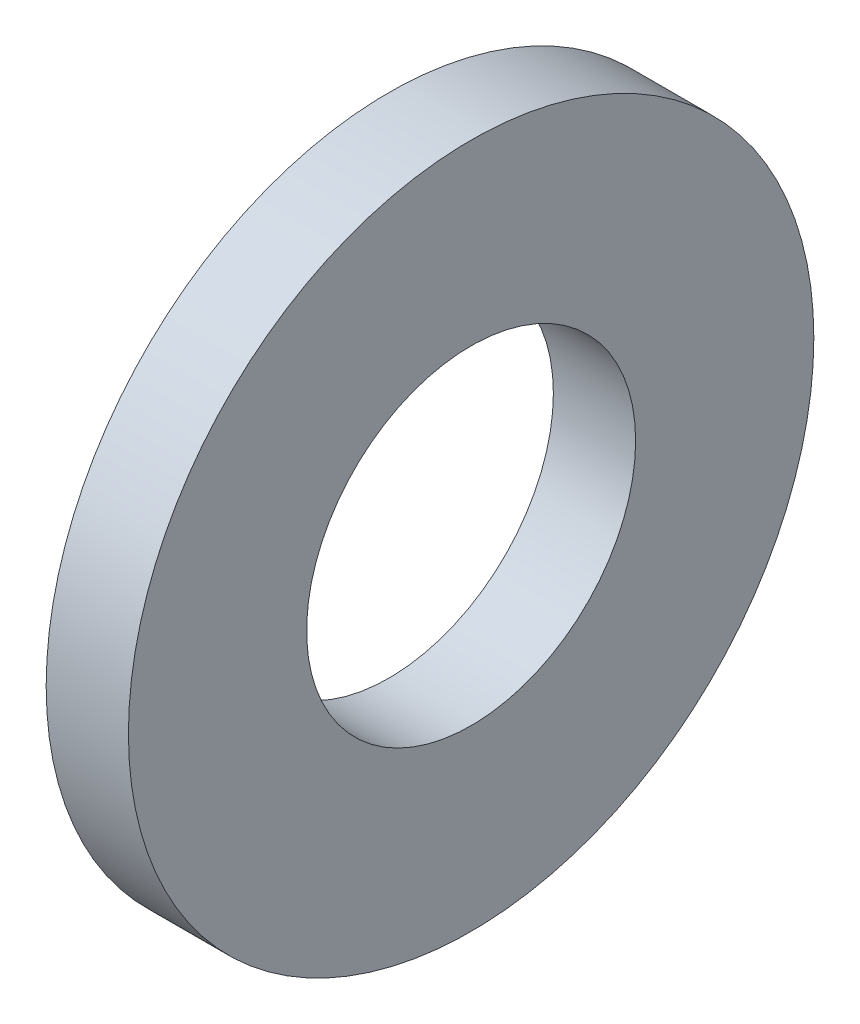
SolidWorks part; units mm, degrees
ref_plane "Front Plane" through (0, 0, 0) normal (0, 0, 1) x (1, 0, 0)
ref_plane "Top Plane" through (0, 0, 0) normal (0, 1, 0) x (1, 0, 0)
ref_plane "Right Plane" through (0, 0, 0) normal (1, 0, 0) x (0, 0, -1)
sketch "Sketch1" plane through (0, 0, 0) normal (1, 0, 0) x (0, 0, -1)
  circle A0 centre (0, 0) radius 6
  circle A1 centre (0, 0) radius 12.5
  dimension "D1" = 12
  dimension "D2" = 25
extrude "Boss-Extrude1" add sketch "Sketch1" along normal blind 3
